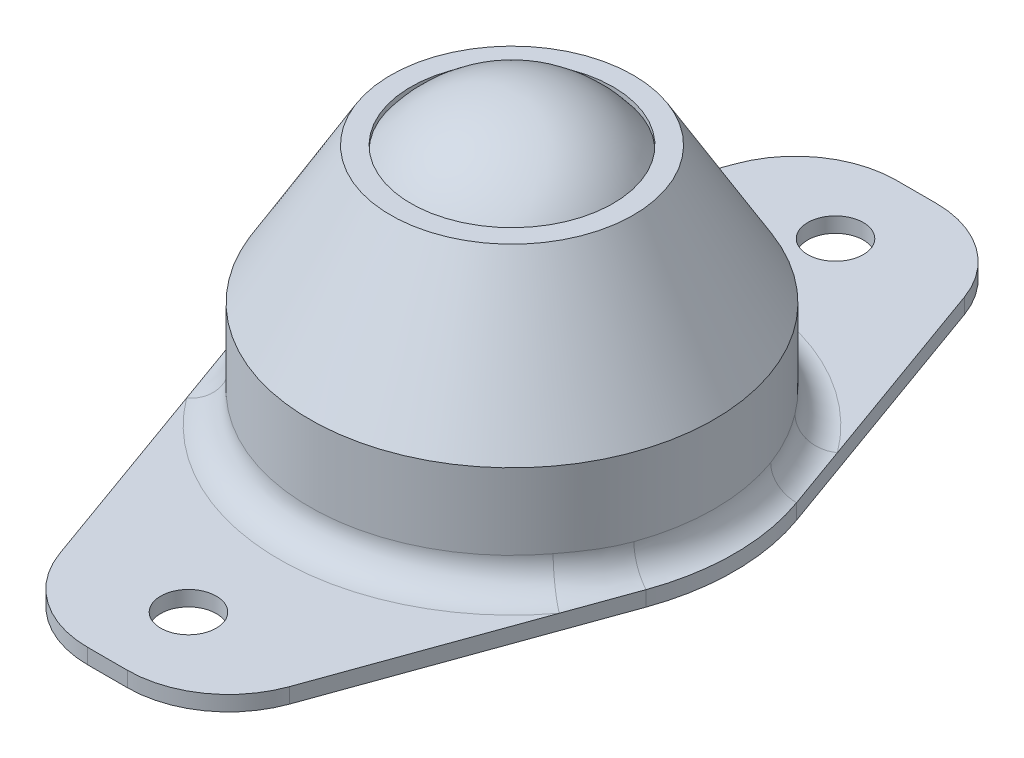
SolidWorks part; units mm, degrees
ref_plane "Front Plane" through (0, 0, 0) normal (0, 0, 1) x (1, 0, 0)
ref_plane "Top Plane" through (0, 0, 0) normal (0, 1, 0) x (1, 0, 0)
ref_plane "Right Plane" through (0, 0, 0) normal (1, 0, 0) x (0, 0, -1)
sketch "Sketch1" plane through (0, 0, 0) normal (0, 0, 1) x (1, 0, 0)
  line L0 (0, 0) -> (0, 30)
  line L1 (0, 0) -> (20, 0)
  line L2 (20, 0) -> (20, 12)
  line L3 (20, 12) -> (12, 25.5)
  line L4 (12, 25.5) -> (10, 25.5)
  line L5 (10, 25.5) -> (10, 25)
  circle A0 centre (0, 17.5) radius 12.5
  dimension "D2" = 20
  dimension "D6" = 25
  dimension "D1" = 30
  dimension "D3" = 2
  dimension "D4" = 0.5
  dimension "D5" = 10
  dimension "D7" = 12
revolve "Revolve1" add sketch "Sketch1" angle 360 about L0
sketch "Sketch2" plane through (0, 0, 0) normal (0, 1, 0) x (1, 0, 0)
  line L0 (-20.7031, 7.4418) -> (-11.3786, 33.3826)
  line L1 (-1.9681, 40) -> (1.9681, 40)
  line L2 (11.3786, 33.3826) -> (20.7031, 7.4418)
  line L3 (0, 0) -> (22, 0) construction
  line L4 (0, 0) -> (0, 40) construction
  circle A0 centre (0, 0) radius 20 construction
  circle A1 centre (0, 0) radius 20
  circle A2 centre (0, 0) radius 22
  circle A3 centre (0, 32) radius 2.75
  arc A4 (1.9681, 40) -> (11.3786, 33.3826) centre (1.9681, 30) cw
  arc A5 (-11.3786, 33.3826) -> (-1.9681, 40) centre (-1.9681, 30) cw
  point P15 (9, 40)
  point P18 (-9, 40)
  dimension "D4" = 8
  dimension "D5" = 5.5
  dimension "D6" = 10
  dimension "D2" = 40
  dimension "D3" = 18
  dimension "D1" = 2
extrude "Boss-Extrude1" add sketch "Sketch2" along normal blind 1.5 contours A5 L0 A2 L2 A4 L1 A3
mirror "Mirror1" about plane through (0, 0, 0) normal (0, 0, 1) of "Boss-Extrude1"
fillet "Fillet1" radius 3 1 edges at (0, 1.5, 20)
